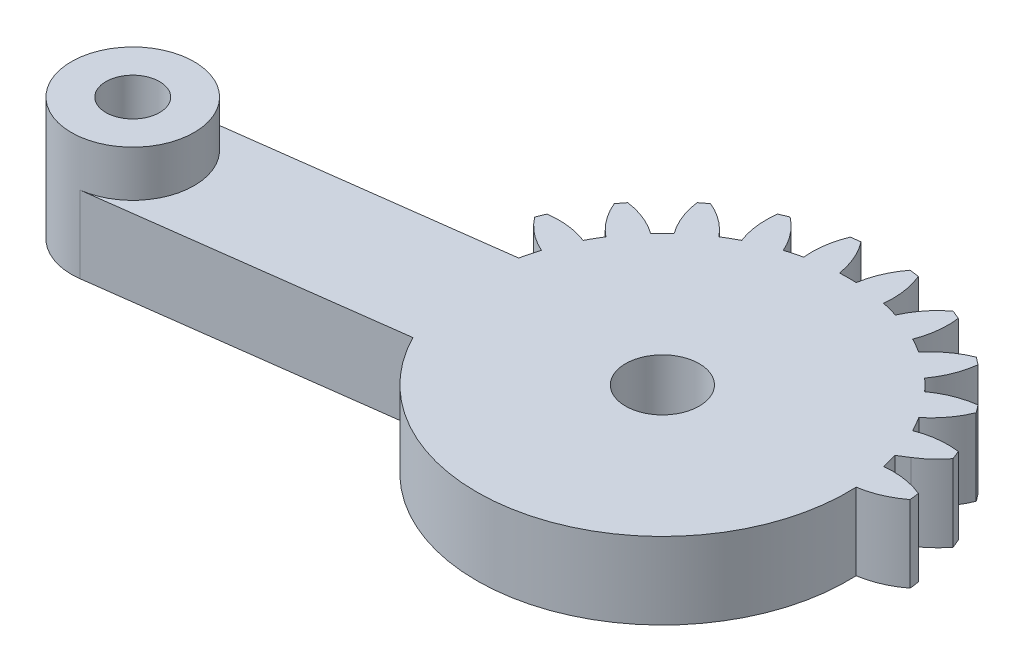
SolidWorks part; units mm, degrees
ref_plane "Front Plane" through (0, 0, 0) normal (0, 0, 1) x (1, 0, 0)
ref_plane "Top Plane" through (0, 0, 0) normal (0, 1, 0) x (1, 0, 0)
ref_plane "Right Plane" through (0, 0, 0) normal (1, 0, 0) x (0, 0, -1)
ref_plane "Plane1" through (0, 4, 0) normal (0, 1, 0) x (1, 0, 0)
sketch "Sketch1" plane through (0, 4, 0) normal (0, 1, 0) x (1, 0, 0)
  line L0 (1.4381, 3.6001) -> (2.0816, 4)
  line L1 (-21.9429, 2.4762) -> (-41.1154, -0.0479)
  line L2 (-40.0712, -7.9795) -> (-20.8986, -5.4553)
  circle A0 centre (-40.5933, -4.0137) radius 1.75
  arc A1 (4.3495, 2.2179) -> (1.7031, 2.6025) centre (2.274, -2.7673) ccw
  arc A2 (1.7031, 2.6025) -> (1.4381, 3.6001) centre (-10.1063, 0) ccw
  arc A3 (2.0816, 4) -> (3.5217, 5.3071) centre (-0.7683, 8.5867) ccw
  arc A4 (3.5217, 5.3071) -> (3.2829, 5.8838) centre (-10.1063, 0) ccw
  arc A5 (3.2829, 5.8838) -> (0.6271, 5.5703) centre (2.5684, 0.5313) ccw
  arc A6 (0.6271, 5.5703) -> (0.0844, 6.5103) centre (-10.1063, 0) ccw
  arc A7 (0.0844, 6.5103) -> (1.6838, 8.6535) centre (-3.3089, 10.711) ccw
  arc A8 (1.6838, 8.6535) -> (1.3038, 9.1487) centre (-10.1063, 0) ccw
  arc A9 (1.3038, 9.1487) -> (-1.1803, 8.1585) centre (1.999, 3.7936) ccw
  arc A10 (-1.1803, 8.1585) -> (-1.9479, 8.926) centre (-10.1063, 0) ccw
  arc A11 (-1.9479, 8.926) -> (-0.9576, 11.4102) centre (-6.3127, 12.1053) ccw
  arc A12 (-0.9576, 11.4102) -> (-1.4528, 11.7901) centre (-10.1063, 0) ccw
  arc A13 (-1.4528, 11.7901) -> (-3.596, 10.1907) centre (0.6046, 6.7975) ccw
  arc A14 (-3.596, 10.1907) -> (-4.5361, 10.7334) centre (-10.1063, 0) ccw
  arc A15 (-4.5361, 10.7334) -> (-4.2225, 13.3892) centre (-9.5751, 12.6747) ccw
  arc A16 (-4.2225, 13.3892) -> (-4.7992, 13.6281) centre (-10.1063, 0) ccw
  arc A17 (-4.7992, 13.6281) -> (-6.4554, 11.5285) centre (-1.5196, 9.3381) ccw
  arc A18 (-6.4554, 11.5285) -> (-7.5039, 11.8094) centre (-10.1063, 0) ccw
  arc A19 (-7.5039, 11.8094) -> (-7.8884, 14.4558) centre (-12.8736, 12.3803) ccw
  arc A20 (-7.8884, 14.4558) -> (-8.5072, 14.5373) centre (-10.1063, 0) ccw
  arc A21 (-8.5072, 14.5373) -> (-9.5636, 12.0806) centre (-4.2291, 11.2423) ccw
  arc A22 (-9.5636, 12.0806) -> (-10.6491, 12.0806) centre (-10.1063, 0) ccw
  arc A23 (-10.6491, 12.0806) -> (-11.7054, 14.5373) centre (-15.9836, 11.2423) ccw
  arc A24 (-11.7054, 14.5373) -> (-12.3243, 14.4558) centre (-10.1063, 0) ccw
  arc A25 (-12.3243, 14.4558) -> (-12.7088, 11.8094) centre (-7.3391, 12.3803) ccw
  arc A26 (-12.7088, 11.8094) -> (-13.7573, 11.5285) centre (-10.1063, 0) ccw
  arc A27 (-13.7573, 11.5285) -> (-15.4135, 13.6281) centre (-18.6931, 9.3381) ccw
  arc A28 (-15.4135, 13.6281) -> (-15.9901, 13.3892) centre (-10.1063, 0) ccw
  arc A29 (-15.9901, 13.3892) -> (-15.6766, 10.7334) centre (-10.6376, 12.6747) ccw
  arc A30 (-15.6766, 10.7334) -> (-16.6166, 10.1907) centre (-10.1063, 0) ccw
  arc A31 (-16.6166, 10.1907) -> (-18.7599, 11.7901) centre (-20.8173, 6.7975) ccw
  arc A32 (-18.7599, 11.7901) -> (-19.255, 11.4102) centre (-10.1063, 0) ccw
  arc A33 (-19.255, 11.4102) -> (-18.2648, 8.926) centre (-13.9, 12.1053) ccw
  arc A34 (-18.2648, 8.926) -> (-19.0324, 8.1585) centre (-10.1063, 0) ccw
  arc A35 (-19.0324, 8.1585) -> (-21.5165, 9.1487) centre (-22.2117, 3.7936) ccw
  arc A36 (-21.5165, 9.1487) -> (-21.8965, 8.6535) centre (-10.1063, 0) ccw
  arc A37 (-21.8965, 8.6535) -> (-20.2971, 6.5103) centre (-16.9038, 10.711) ccw
  arc A38 (-20.2971, 6.5103) -> (-20.8398, 5.5703) centre (-10.1063, 0) ccw
  arc A39 (-20.8398, 5.5703) -> (-23.4956, 5.8838) centre (-22.7811, 0.5313) ccw
  arc A40 (-23.4956, 5.8838) -> (-23.7344, 5.3071) centre (-10.1063, 0) ccw
  arc A41 (-23.7344, 5.3071) -> (-21.6348, 3.6509) centre (-19.4444, 8.5867) ccw
  arc A42 (-21.6348, 3.6509) -> (-21.9429, 2.4762) centre (-10.1063, 0) ccw
  arc A43 (-41.1154, -0.0479) -> (-40.0712, -7.9795) centre (-40.5933, -4.0137) ccw
  arc A44 (-20.8986, -5.4553) -> (1.9742, 0.5427) centre (-10.1063, 0) ccw
  arc A45 (1.9742, 0.5427) -> (4.431, 1.5991) centre (1.1359, 5.8773) ccw
  arc A46 (4.431, 1.5991) -> (4.3495, 2.2179) centre (-10.1063, 0) ccw
  circle A47 centre (-10.1063, 0) radius 2.4
  dimension "D1" = 3.5
  dimension "D3" = 4.8
  dimension "D5" = 5.4
  dimension "D6" = 12.0927
  dimension "D7" = 5.4
  dimension "D8" = 14.625
  dimension "D9" = 5.4
  dimension "D10" = 0.0844
  dimension "D11" = 5.4
  dimension "D12" = 0.6046
  dimension "D13" = 5.4
  dimension "D14" = 0.6271
  dimension "D15" = 5.4
  dimension "D16" = 1.1359
  dimension "D17" = 5.4
  dimension "D18" = 1.3038
  dimension "D19" = 5.4
  dimension "D20" = 1.4381
  dimension "D21" = 5.4
  dimension "D22" = 1.6838
  dimension "D23" = 5.4
  dimension "D24" = 1.7031
  dimension "D25" = 5.4
  dimension "D26" = 1.9742
  dimension "D27" = 5.4
  dimension "D28" = 1.999
  dimension "D29" = 5.4
  dimension "D30" = 2.0816
  dimension "D31" = 5.4
  dimension "D32" = 2.274
  dimension "D33" = 5.4
  dimension "D34" = 2.5684
  dimension "D35" = 5.4
  dimension "D36" = 3.2829
  dimension "D37" = 5.4
  dimension "D38" = 3.5217
  dimension "D39" = 5.4
  dimension "D40" = 0.9576
  dimension "D41" = 5.4
  dimension "D42" = 1.4528
  dimension "D43" = 5.4
  dimension "D44" = 1.5196
  dimension "D45" = 5.4
  dimension "D46" = 1.9479
  dimension "D47" = 4
  dimension "D48" = 4.2225
  dimension "D49" = 5.4
  dimension "D50" = 4.2291
  dimension "D51" = 4.5361
  dimension "D52" = 4.7992
  dimension "D54" = 7.3391
  dimension "D55" = 7.5039
  dimension "D56" = 7.8884
  dimension "D57" = 8.5072
  dimension "D58" = 10.6376
  dimension "D59" = 10.6491
  dimension "D60" = 11.7054
  dimension "D61" = 12.3243
  dimension "D62" = 13.7573
  dimension "D63" = 13.9
  dimension "D65" = 15.4135
  dimension "D66" = 15.6766
  dimension "D67" = 16.6166
  dimension "D68" = 16.9038
  dimension "D69" = 18.2648
  dimension "D70" = 18.7599
  dimension "D71" = 19.0324
  dimension "D72" = 19.4444
  dimension "D73" = 20.2971
  dimension "D74" = 20.8398
  dimension "D75" = 20.8986
  dimension "D76" = 21.5165
  dimension "D77" = 21.6348
  dimension "D78" = 21.9429
  dimension "D79" = 22.7811
  dimension "D80" = 40.0712
  dimension "D81" = 40.5933
  dimension "D82" = 0.5313
extrude "Boss-Extrude1" add sketch "Sketch1" against normal blind 5
sketch "草图1" plane through (0, 4, 0) normal (0, 1, 0) x (1, 0, 0)
  circle A0 centre (-40.5933, -4.0137) radius 1.75
  circle A2 centre (-40.5933, -4.0137) radius 4
extrude "凸台-拉伸1" add sketch "草图1" along normal blind 3
ref_point "点1"
